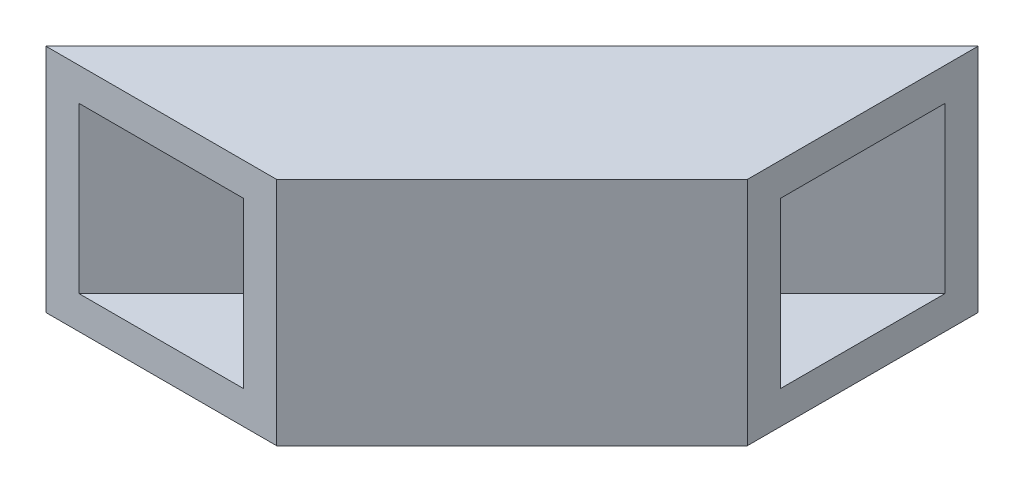
SolidWorks part; units mm, degrees
ref_plane "Alzado" through (0, 0, 0) normal (0, 0, 1) x (1, 0, 0)
ref_plane "Planta" through (0, 0, 0) normal (0, 1, 0) x (1, 0, 0)
ref_plane "Vista lateral" through (0, 0, 0) normal (1, 0, 0) x (0, 0, -1)
sketch "Croquis1" plane through (0, 0, 0) normal (0, 0, 1) x (1, 0, 0)
  line L1 (-7.5, -7.5) -> (7.5, -7.5)
  line L2 (-7.5, -7.5) -> (-7.5, 7.5)
  line L3 (-7.5, 7.5) -> (7.5, 7.5)
  line L4 (7.5, -7.5) -> (7.5, 7.5)
  line L5 (-7.5, -7.5) -> (7.5, 7.5) construction
  line L6 (-7.5, 7.5) -> (7.5, -7.5) construction
  line L7 (-10.5, -10.5) -> (10.5, -10.5)
  line L8 (-10.5, -10.5) -> (-10.5, 10.5)
  line L9 (-10.5, 10.5) -> (10.5, 10.5)
  line L10 (10.5, -10.5) -> (10.5, 10.5)
  line L11 (-10.5, -10.5) -> (10.5, 10.5) construction
  line L12 (-10.5, 10.5) -> (10.5, -10.5) construction
  point P0 (0, 0)
  point P6 (0, 0)
  dimension "D1" = 15
  dimension "D2" = 15
  dimension "D3" = 21
  dimension "D4" = 21
extrude "Saliente-Extruir1" add sketch "Croquis1" along normal blind 70
sketch "Croquis5" plane through (0, 0, 0) normal (0, 1, 0) x (1, 0, 0)
  line L0 (0, 0) -> (24.6662, 24.6662) construction
  line L1 (10.5, 0) -> (-10.5, 0) construction
  dimension "D1" = 45
sketch "Croquis6" plane through (0, 0, 0) normal (0, 0, -1) x (-1, 0, 0)
  line L1 (-7.5, -7.5) -> (7.5, -7.5)
  line L2 (-7.5, -7.5) -> (-7.5, 7.5)
  line L3 (-7.5, 7.5) -> (7.5, 7.5)
  line L4 (7.5, -7.5) -> (7.5, 7.5)
  line L5 (-7.5, -7.5) -> (7.5, 7.5) construction
  line L6 (-7.5, 7.5) -> (7.5, -7.5) construction
  line L7 (-10.5, -10.5) -> (10.5, -10.5)
  line L8 (-10.5, -10.5) -> (-10.5, 10.5)
  line L9 (-10.5, 10.5) -> (10.5, 10.5)
  line L10 (10.5, -10.5) -> (10.5, 10.5)
  line L11 (-10.5, -10.5) -> (10.5, 10.5) construction
  line L12 (-10.5, 10.5) -> (10.5, -10.5) construction
  point P0 (0, 0)
  point P7 (0, 0)
extrude "Saliente-Extruir2" add sketch "Croquis6" along direction (0.7071, 0, -0.7071) on the side of the normal blind 60
sketch "Croquis7" plane through (0, 10.5, 0) normal (0, 1, 0) x (1, 0, 0)
  line L0 (31.9264, 42.4264) -> (31.9264, 21.4264)
  line L1 (52.9264, 42.4264) -> (10.5, 0) construction
  line L2 (31.9264, 21.4264) -> (52.9264, 42.4264)
  line L3 (52.9264, 42.4264) -> (31.9264, 42.4264)
extrude "Cortar-Extruir2" cut sketch "Croquis7" against normal through all
sketch "Croquis8" plane through (31.9264, 0, 0) normal (1, 0, 0) x (0, 0, -1)
  line L1 (39.4264, 7.5) -> (24.4264, 7.5)
  line L2 (39.4264, 7.5) -> (39.4264, -7.5)
  line L3 (39.4264, -7.5) -> (24.4264, -7.5)
  line L4 (24.4264, 7.5) -> (24.4264, -7.5)
  line L5 (42.4264, 10.5) -> (21.4264, 10.5)
  line L6 (42.4264, 10.5) -> (42.4264, -10.5)
  line L7 (42.4264, -10.5) -> (21.4264, -10.5)
  line L8 (21.4264, 10.5) -> (21.4264, -10.5)
extrude "Saliente-Extruir3" add sketch "Croquis8" along normal blind 60
sketch "Croquis9" plane through (0, 10.5, 0) normal (0, 1, 0) x (1, 0, 0)
  line L1 (-10.5, 0) -> (10.5, 0)
  line L2 (-10.5, 0) -> (-10.5, -70)
  line L3 (-10.5, -70) -> (10.5, -70)
  line L4 (10.5, 0) -> (10.5, -70)
  line L5 (31.9264, 42.4264) -> (91.9264, 42.4264)
  line L6 (31.9264, 42.4264) -> (31.9264, 21.4264)
  line L7 (31.9264, 21.4264) -> (91.9264, 21.4264)
  line L8 (91.9264, 42.4264) -> (91.9264, 21.4264)
extrude "Cortar-Extruir3" cut sketch "Croquis9" against normal through all
